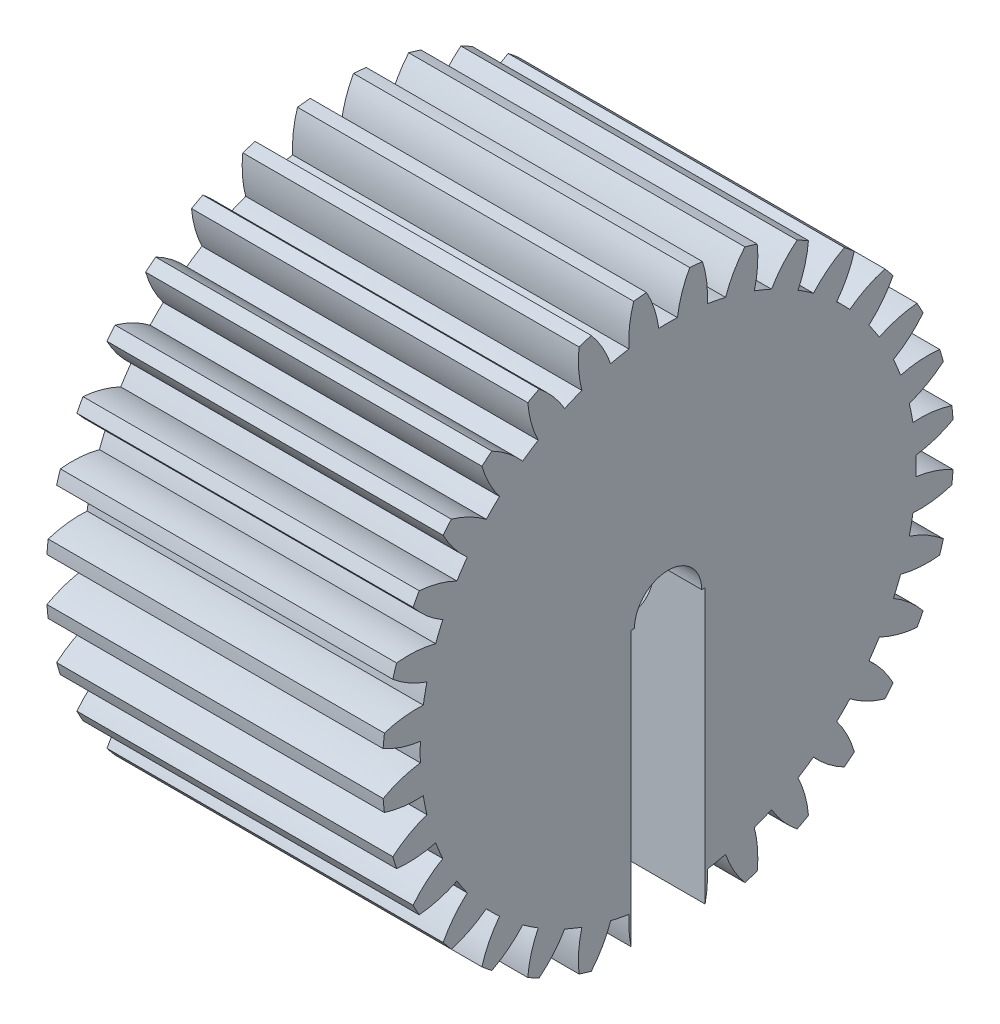
SolidWorks part; units mm, degrees
ref_plane "Plane1" through (0, 0, 0) normal (0, 0, 1) x (1, 0, 0)
ref_plane "Plane2" through (0, 0, 0) normal (0, 1, 0) x (1, 0, 0)
ref_plane "Plane3" through (0, 0, 0) normal (1, 0, 0) x (0, 0, -1)
other "Configuration Table"
sketch "HoldingSke" plane through (0, 0, 0) normal (0, 1, 0) x (1, 0, 0)
  line L0 (0, 0) -> (1.6961, -1.0598)
  line L1 (-15, 0) -> (100, 0) construction
  line L2 (0, 0) -> (-2.1039, 2.3779)
  line L3 (0, 0) -> (-11.863, 4.5341)
  line L4 (0, 0) -> (7.3237, 4.5764)
  line L5 (0, 0) -> (-46.8476, -17.4728)
  line L6 (0, 0) -> (-8.2896, -5.593)
  line L7 (-2.1039, 2.3779) -> (8.6586, 51.2059)
  line L8 (-76.2, 54.61) -> (-75.9, 54.61)
  line L9 (-67.7845, 28.3722) -> (-49.3413, 33.142)
  line L10 (-76.2, 71.12) -> (104.1128, 71.12)
  line L11 (0, 0) -> (-10, 0)
  line L12 (-76.2, 101.6) -> (-76.181, 101.6)
  line L13 (24.9733, 27.94) -> (52.9518, 28.4284)
  line L14 (24.9733, 27.94) -> (24.9743, 27.94)
  line L15 (24.9733, 27.94) -> (100.4006, 29.5858)
  line L16 (-63.627, -0.5) -> (-12.827, -0.5)
  circle A0 centre (0, 0) radius 1
  circle A1 centre (0, 0) radius 7.374
  circle A2 centre (0, 0) radius 37.5
  circle A3 centre (0, 0) radius 1
  dimension "MHD" = 14.748
  dimension "Hub_dia" = 75
  dimension "Bore" = 2
  dimension "MBD" = 2
  dimension "Num_teeth" = 32
  dimension "Pitch" = 2
  dimension "Overall_len" = 50
  dimension "Show_teeth" = 32
  dimension "Thickness" = 10
  dimension "OAL" = 50.0001
  dimension "T_dim" = 0.3
  dimension "Ap" = 14.5
  dimension "H" = 19.05
  dimension "Pitch_radius" = 180.3128
  dimension "Width" = 10
  dimension "Backlash" = 0.019
  dimension "Addendum_fac" = 1
  dimension "Dedendum_fac" = 1.25
  dimension "Clearance_fac" = 0.25
  dimension "Dedendum_add" = 0.001
  dimension "Module" = 0.5
sketch "BasProSke" plane through (0, 0, 0) normal (0, 1, 0) x (1, 0, 0)
  line L0 (-10, 0) -> (60, 0) construction
  line L1 (0, 0) -> (0, 8.5)
  line L2 (0, 0) -> (10, 0)
  line L3 (10, 0) -> (10, 8.5)
  line L4 (10, 8.5) -> (0, 8.5)
  dimension "Thickness" = 10
  dimension "Diameter" = 17
revolve "Base-Revolve" add sketch "BasProSke" angle 360 about L0
sketch "TooCutSke" plane through (0, 0, 0) normal (1, 0, 0) x (0, 0, -1)
  line L1 (0, 0) -> (0, 107) construction
  line L2 (0, 0) -> (-0.4258, 7.9887) construction
  line L3 (0, 0) -> (-1.5667, 15.9069) construction
  line L4 (-0.4258, 7.9887) -> (-0.7833, 7.9534) construction
  arc A0 (0.277, 7.3688) -> (-0.277, 7.3688) centre (0, 0) ccw
  arc A1 (0.6561, 8.5001) -> (-0.6561, 8.5001) centre (0, 0) ccw
  circle A2 centre (0, 0) radius 8 construction
  circle A3 centre (0, 0) radius 7.7452 construction
  arc A4 (-0.277, 7.3688) -> (-0.6561, 8.5001) centre (-3.4475, 6.9356) ccw
  arc A5 (0.6561, 8.5001) -> (0.277, 7.3688) centre (3.4475, 6.9356) ccw
  dimension "Root_dia" = 14.748
  dimension "Overcut_dia" = 17.0508
  dimension "Pitch_dia" = 16
  dimension "Base_dia" = 15.4904
  dimension "Flank_rad" = 3.2
  dimension "Half_ang" = 5.625
  dimension "Half_CT" = 0.3593
extrude "ToothCut" cut sketch "TooCutSke" along normal through all
fillet "Breaks" [suppressed] radius 0.01
fillet "RootFillets" [suppressed] radius 0.126
pattern_circular "TeethCuts" count 32 every 11.25 about axis through (-10, 0, 0) along (1, 0, 0) of "ToothCut", "RootFillets", "Breaks"
sketch "HubNeaOneSke" plane through (0, 0, 0) normal (-1, 0, 0) x (0, 0, 1)
  circle A0 centre (0, 0) radius 7.374
  dimension "Diameter" = 14.748
extrude "HubNearOne" [suppressed] add sketch "HubNeaOneSke" along normal blind 40.0001
sketch "HubNeaBotSke" plane through (0, 0, 0) normal (-1, 0, 0) x (0, 0, 1)
  circle A0 centre (0, 0) radius 7.374
  dimension "Diameter" = 14.748
extrude "HubNearBoth" [suppressed] add sketch "HubNeaBotSke" along normal blind 20
ref_plane "FarPln" through (10, 0, 0) normal (1, 0, 0) x (0, 0, -1)
sketch "HubFarSke" plane through (10, 0, 0) normal (1, 0, 0) x (0, 0, -1)
  circle A0 centre (0, 0) radius 7.374
  dimension "Diameter" = 14.748
extrude "HubFar" [suppressed] add sketch "HubFarSke" along normal blind 20
sketch "BorSke" plane through (0, 0, 0) normal (1, 0, 0) x (0, 0, -1)
  circle A0 centre (0, 0) radius 1
  dimension "Diameter" = 2
extrude "Bore" cut sketch "BorSke" along normal mid plane 100.0001
sketch "KeySke" plane through (0, 0, 0) normal (1, 0, 0) x (0, 0, -1)
  line L0 (-0.4, 0) -> (-0.4, 1.3)
  line L1 (-0.4, 1.3) -> (0.4, 1.3)
  line L2 (0.4, 1.3) -> (0.4, 0)
  line L3 (0, 0) -> (0, 34) construction
  line L4 (-0.4, 0) -> (0.4, 0)
  dimension "Offset" = 1.3
  dimension "Width" = 0.8
extrude "Keyway" [suppressed] cut sketch "KeySke" along normal mid plane 100.0001
pattern_circular "Keyway2" [suppressed] count 2 every 90 about axis through (-10, 0, 0) along (1, 0, 0)
sketch "Sketch1" plane through (10, 0, 0) normal (1, 0, 0) x (0, 0, -1)
  line L1 (-1.1, 0) -> (1.1, 0)
  line L2 (-1.1, 0) -> (-1.1, -12)
  line L3 (-1.1, -12) -> (1.1, -12)
  line L4 (1.1, 0) -> (1.1, -12)
  circle A0 centre (0, 0) radius 1 construction
  point P6 (0, 0)
  dimension "D3" = 12
  dimension "D1" = 2.2
  dimension "D2" = 1.1
  dimension "D4" = 12
extrude "Cut-Extrude1" cut sketch "Sketch1" against normal through all
sketch "Sketch2" plane through (0, 0, 0) normal (0, 0, 1) x (1, 0, 0)
  line L3 (3.25, 0) -> (8.75, 0)
  arc A0 (8.75, 0) -> (3.25, 0) centre (6, 0) ccw
  dimension "D2" = 5.5
  dimension "D1" = 6
revolve "Cut-Revolve1" cut sketch "Sketch2" angle 360 about L3
ref_plane "Plane4" through (3, 0, 0) normal (-1, 0, 0) x (0, 0, 1)
sketch "Sketch4" plane through (3, 0, 0) normal (-1, 0, 0) x (0, 0, 1)
  circle A0 centre (0, 0) radius 1.125
  circle A1 centre (0, 0) radius 0.5
  dimension "D1" = 1
extrude "Boss-Extrude1" add sketch "Sketch4" along normal blind 0.5
sketch "Sketch5" plane through (0, 0, -1.1) normal (0, 0, 1) x (1, 0, 0)
  line L0 (0, -8.1488) -> (10, -8.1488) construction
  line L1 (0, 0) -> (2.5, 0)
  line L2 (0, 0) -> (0, -8.1488)
  line L3 (0, -8.1488) -> (2.5, -8.1488)
  line L4 (2.5, 0) -> (2.5, -8.1488)
  dimension "D1" = 2.5
extrude "Boss-Extrude2" add sketch "Sketch5" along normal up to next
sketch "Sketch6" plane through (0, 0, 0) normal (-1, 0, 0) x (0, 0, 1)
  line L0 (1, 0) -> (-1, 0) construction
  circle A0 centre (0, 0) radius 1.125
  dimension "D1" = 2.25
extrude "Cut-Extrude4" cut sketch "Sketch6" against normal blind 2.45
sketch "Sketch7" plane through (2.5, 0, 0) normal (1, 0, 0) x (0, 0, -1)
  circle A0 centre (0, 0) radius 0.5
extrude "Cut-Extrude5" cut sketch "Sketch7" against normal blind 2.4
equation "' \"Module@HoldingSke\" = 6.35"
equation "' \"Num_teeth@HoldingSke\" = 12"
equation "' \"Ap@HoldingSke\" =  20"
equation "' \"Ap@HoldingSke\" = 20"
equation "' \"Width@HoldingSke\" = 0.5 * 25.4"
equation "' \"Hub_dia@HoldingSke\"= 1 * 25.4"
equation "' \"Hub_dia@HoldingSke\" = 1 * 25.4"
equation "' \"Overall_len@HoldingSke\" = 1.0 * 25.4"
equation "' \"Bore@HoldingSke\" = 0.75 * 25.4"
equation "' \"T_dim@HoldingSke\" = 0.1 * 25.4"
equation "' \"Width@KeySke\" = 0.25 * 25.4"
equation "' \"Show_teeth@HoldingSke\" = 13"
equation "' \"Backlash@HoldingSke\" = 0.009 * 25.4"
equation "' \"Addendum_fac@HoldingSke\" = 1.0"
equation "' \"Dedendum_fac@HoldingSke\" = 1.25"
equation "' \"Dedendum_add@HoldingSke\" = 0.00005 * 25.4"
equation "' \"Clearance_fac@HoldingSke\" = 0.25"
equation "\"Pitch@HoldingSke\" = 1 / \"Module@HoldingSke\""
equation "\"Overcut_dia@TooCutSke\" = (\"Num_teeth@HoldingSke\" + 2 * \"Addendum_fac@HoldingSke\") / \"Pitch@HoldingSke\" + 0.002 * 25.4"
equation "\"Pitch_dia@TooCutSke\" = \"Num_teeth@HoldingSke\" / \"Pitch@HoldingSke\""
equation "\"Base_dia@TooCutSke\" = \"Num_teeth@HoldingSke\" / \"Pitch@HoldingSke\" * cos((\"Ap@HoldingSke\"  * 3.14159265 / 180))"
equation "\"Root_dia@TooCutSke\" = (\"Num_teeth@HoldingSke\" + 2) / \"Pitch@HoldingSke\" - 2 * (\"Addendum_fac@HoldingSke\" + \"Dedendum_fac@HoldingSke\") / \"Pitch@HoldingSke\" - \"Dedendum_add@HoldingSke\" * 2"
equation "\"Half_ang@TooCutSke\" = 180 / \"Num_teeth@HoldingSke\""
equation "\"Half_CT@TooCutSke\" = \"Num_teeth@HoldingSke\" / \"Pitch@HoldingSke\" * sin((3.14159265 / 2 / \"Num_teeth@HoldingSke\")) / 2 - 7 * \"Backlash@HoldingSke\" / 4"
equation "\"Flank_rad@TooCutSke\" = \"Num_teeth@HoldingSke\" / \"Pitch@HoldingSke\" / 5"
equation "\"Radius@RootFillets\" = \"Clearance_fac@HoldingSke\" / \"Pitch@HoldingSke\" + \"Dedendum_add@HoldingSke\""
equation "\"Break_rad@Breaks\" = 0.02 / \"Pitch@HoldingSke\""
equation "\"Thickness@HoldingSke\" = \"Width@HoldingSke\""
equation "\"OAL@HoldingSke\" = \"Thickness@HoldingSke\""
equation "\"MHD@HoldingSke\" = (\"Num_teeth@HoldingSke\" + 2) / \"Pitch@HoldingSke\" - 2 * (\"Addendum_fac@HoldingSke\" + \"Dedendum_fac@HoldingSke\")  / \"Pitch@HoldingSke\" - \"Dedendum_add@HoldingSke\" * 2"
equation "\"MBD@HoldingSke\" = (\"Num_teeth@HoldingSke\" + 2) / \"Pitch@HoldingSke\" - 2 * (\"Addendum_fac@HoldingSke\" + \"Dedendum_fac@HoldingSke\")  / \"Pitch@HoldingSke\" - \"Dedendum_add@HoldingSke\" * 2 - 0.002 * 25.4"
equation "\"MHD@HoldingSke\" = ((sgn( \"MHD@HoldingSke\" - \"Hub_dia@HoldingSke\" )-1)*( \"MHD@HoldingSke\" - \"Hub_dia@HoldingSke\" ))/-2+ \"Hub_dia@HoldingSke\""
equation "\"MBD@HoldingSke\" = ((sgn( \"MBD@HoldingSke\" - \"Bore@HoldingSke\" )-1)*( \"MBD@HoldingSke\" - \"Bore@HoldingSke\" ))/-2+ \"Bore@HoldingSke\""
equation "\"OAL@HoldingSke\" = ((sgn( \"OAL@HoldingSke\" - \"Overall_len@HoldingSke\" )+1)*( \"OAL@HoldingSke\" - \"Overall_len@HoldingSke\" ))/2 + \"Overall_len@HoldingSke\" + 0.000002 * 25.4"
equation "\"Num_teeth@TeethCuts\" = int( \"Show_teeth@HoldingSke\" ) + 1"
equation "\"Num_teeth@TeethCuts\" = ((sgn( \"Num_teeth@TeethCuts\" - \"Num_teeth@HoldingSke\" )-1)*( \"Num_teeth@TeethCuts\" - \"Num_teeth@HoldingSke\" ))/-2+ \"Num_teeth@HoldingSke\""
equation "\"Num_teeth@TeethCuts\" = ((sgn( \"Num_teeth@TeethCuts\" - 2.0)+1)*( \"Num_teeth@TeethCuts\" - 2.0))/2 +2.0"
equation "\"Angle@TeethCuts\" = 360.0 / \"Num_teeth@HoldingSke\""
equation "\"Diameter@BasProSke\" = (\"Num_teeth@HoldingSke\" + 2 * \"Addendum_fac@HoldingSke\") / \"Pitch@HoldingSke\""
equation "\"Thickness@BasProSke\"  = \"Thickness@HoldingSke\""
equation "' \"Fillet_rad@BasProSke\" =  \"Thickness@HoldingSke\" * 0.05"
equation "' \"Fillet_rad@BasProSke\" = \"Thickness@HoldingSke\" * 0.05"
equation "\"MHD@HoldingSke\" = ((sgn( \"MHD@HoldingSke\" - \"Root_dia@TooCutSke\" )-1)*( \"MHD@HoldingSke\" - \"Root_dia@TooCutSke\" ))/-2+ \"Root_dia@TooCutSke\""
equation "\"Diameter@HubNeaOneSke\" = \"MHD@HoldingSke\""
equation "\"Length@HubNearOne\" = \"OAL@HoldingSke\" - \"Thickness@BasProSke\""
equation "\"Diameter@HubNeaBotSke\" = \"MHD@HoldingSke\""
equation "\"Length@HubNearBoth\" = ( \"OAL@HoldingSke\" - \"Thickness@BasProSke\" ) / 2.0"
equation "\"Thickness@FarPln\" = \"Thickness@BasProSke\""
equation "\"Diameter@HubFarSke\" = \"MHD@HoldingSke\""
equation "\"Length@HubFar\" = ( \"OAL@HoldingSke\" - \"Thickness@BasProSke\" ) / 2.0"
equation "\"Diameter@BorSke\" = \"MBD@HoldingSke\""
equation "\"D1@Bore\" = \"OAL@HoldingSke\" * 2.0"
equation "\"D1@Keyway\" = \"OAL@HoldingSke\" * 2.0"
equation "\"Offset@KeySke\" = \"T_dim@HoldingSke\" + \"MBD@HoldingSke\" / 2.0"
